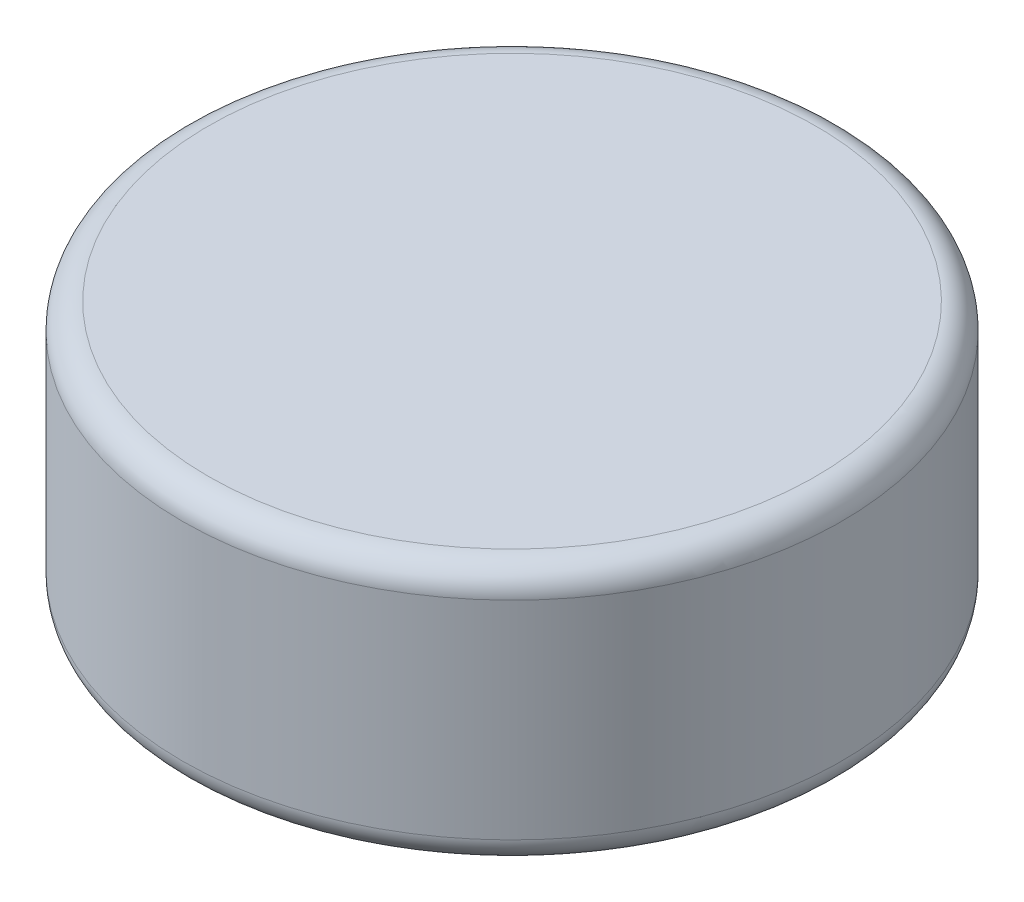
SolidWorks part; units mm, degrees
material "聚亚安酯(11671)"
ref_plane "前视基准面" through (0, 0, 0) normal (0, 0, 1) x (1, 0, 0)
ref_plane "上视基准面" through (0, 0, 0) normal (0, 1, 0) x (1, 0, 0)
ref_plane "右视基准面" through (0, 0, 0) normal (1, 0, 0) x (0, 0, -1)
other "Configuration Table"
sketch "草图1" plane through (0, 0, 0) normal (0, 1, 0) x (1, 0, 0)
  circle A0 centre (0, 0) radius 127
  dimension "D1" = 254
extrude "凸台-拉伸1" add sketch "草图1" along normal blind 100
fillet "圆角1" radius 10 2 edges at (0, 0, 127) (0, 100, 127)
sketch "草图2" plane through (0, 0, 0) normal (0, -1, 0) x (1, 0, 0)
  circle A0 centre (0, 0) radius 64.5
  dimension "D1" = 129
extrude "切除-拉伸1" cut sketch "草图2" against normal blind 39
fillet "圆角2" radius 10 1 edges at (0, 0, -64.5)
